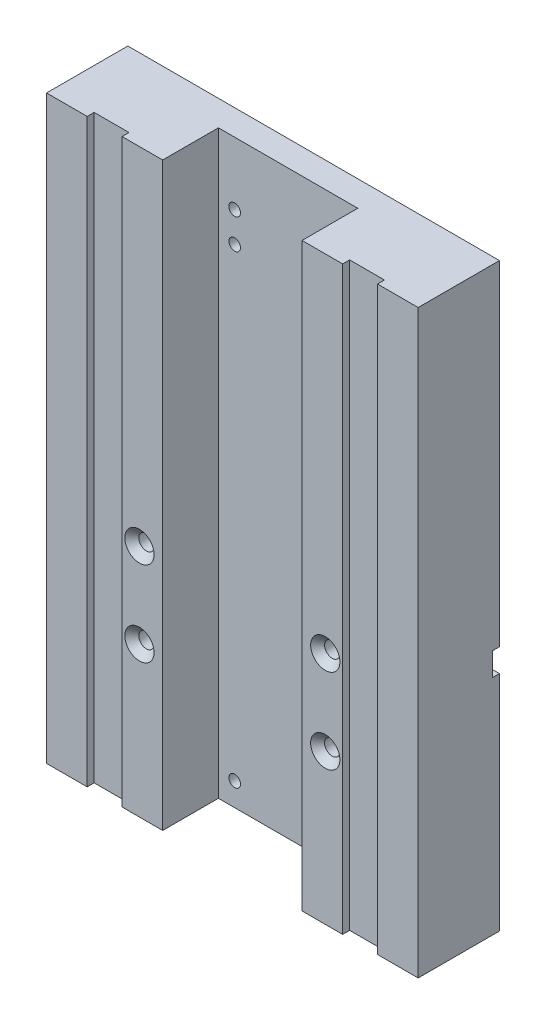
SolidWorks part; units mm, degrees
material "3.1355 (EN-AW 2024)"
ref_plane "Спереди" through (0, 0, 0) normal (0, 0, 1) x (1, 0, 0)
ref_plane "Сверху" through (0, 0, 0) normal (0, 1, 0) x (1, 0, 0)
ref_plane "Справа" through (0, 0, 0) normal (1, 0, 0) x (0, 0, -1)
sketch "Эскиз9" plane through (-20, 0, 0) normal (0, 0, -1) x (-1, 0, 0)
  line L1 (-100, 202) -> (60, 202)
  line L2 (-100, 202) -> (-100, -48)
  line L3 (-100, -48) -> (60, -48)
  line L4 (60, 202) -> (60, -48)
  point P4 (-20, 202)
  point P5 (-20, -48)
  dimension "D1" = 48
  dimension "D2" = 250
  dimension "D3" = 160
extrude "База" add sketch "Эскиз9" along normal blind 35
sketch "Эскиз14" plane through (0, 0, -35) normal (0, 0, -1) x (-1, 0, 0)
  line L0 (-80, 202) -> (-80, -48) construction
  line L1 (-80, 58) -> (80, 58)
  line L2 (-80, 58) -> (-80, 48)
  line L3 (-80, 48) -> (80, 48)
  line L4 (80, 58) -> (80, 48)
  line L5 (80, -48) -> (80, 202) construction
  line L6 (-80, -48) -> (80, -48) construction
  dimension "D1" = 10
  dimension "D2" = 96
extrude "Направляющая" cut sketch "Эскиз14" against normal blind 3
hole_wizard "К плите M6" positions "Эскиз12" profile "Эскиз13" countersink size "M6" standard "DIN" end condition through all
sketch "Эскиз12" plane through (0, 0, 0) normal (0, 0, 1) x (1, 0, 0)
  line L18 (-40, 53) -> (0, 53) construction
  line L19 (0, 53) -> (40, 53) construction
  line L22 (0, 53) -> (0, 58) construction
  line L23 (-80, 58) -> (80, 58) construction
  line L26 (0, 53) -> (0, 48) construction
  line L27 (80, 48) -> (-80, 48) construction
  point P0 (-40, 53)
  point P2 (40, 53)
  point P60 (-40, 16.5)
  point P62 (40, 16.5)
  dimension "D1" = 36.5
  dimension "D2" = 80
sketch "Эскиз13" plane through (-40, 53, 0) normal (1, 0, 0) x (0, -1, 0)
  line L0 (0, 0) -> (0, 35)
  line L1 (0, 35) -> (3.3, 35)
  line L2 (3.3, 35) -> (3.3, 3)
  line L3 (3.3, 3) -> (6.3, 0)
  line L5 (6.3, 0) -> (0, 0)
  line L6 (-3.3, 3) -> (-6.3, 0) construction
  line L11 (0, -6.35) -> (0, 107.95) construction
  dimension "Диаметр сквозного отверстия" = 6.6
  dimension "Глубина сквозного отверстия" = 35
  dimension "Диаметр передней зенковки" = 12.6
  dimension "Угол передней зенковки" = 90
sketch "Эскиз11" plane through (0, 0, 0) normal (0, 0, -1) x (-1, 0, 0)
  line L0 (80, 202) -> (-80, 202) construction
  line L1 (-30, 202) -> (30, 202)
  line L2 (-30, 202) -> (-30, -48)
  line L3 (-30, -48) -> (30, -48)
  line L4 (30, 202) -> (30, -48)
  line L5 (-80, -48) -> (80, -48) construction
  point P8 (0, 202)
  point P9 (0, -48)
  dimension "D1" = 60
extrude "Вырез-ШВП" cut sketch "Эскиз11" along normal blind 24
sketch "Эскиз15" plane through (0, 0, 0) normal (0, 0, 1) x (1, 0, 0)
  line L0 (-30, 102) -> (-47.5, 102) construction
  line L1 (-62.5, 252) -> (-47.5, 252)
  line L2 (-62.5, 252) -> (-62.5, -48)
  line L3 (-62.5, -48) -> (-47.5, -48)
  line L4 (-47.5, 252) -> (-47.5, -48)
  line L7 (62.5, 252) -> (47.5, 252)
  line L8 (62.5, 252) -> (62.5, -48)
  line L9 (62.5, -48) -> (47.5, -48)
  line L10 (47.5, 252) -> (47.5, -48)
  line L11 (-62.5, 102) -> (-80, 102) construction
  line L14 (-30, -48) -> (-80, -48) construction
  line L15 (47.5, 102) -> (30, 102) construction
  line L18 (62.5, 102) -> (80, 102) construction
  line L21 (80, 202) -> (80, -48) construction
  line L22 (30, 202) -> (30, -48) construction
  line L23 (-80, -48) -> (-80, 202) construction
  line L24 (-30, -48) -> (-30, 202) construction
  dimension "D1" = 15
  dimension "D3" = 300
extrude "Рельсы" cut sketch "Эскиз15" against normal blind 3
hole_wizard "Всободный конец ШВП - M6" positions "Эскиз16" profile "Эскиз17" tap size "M6" standard "DIN" end condition through all
sketch "Эскиз16" plane through (0, 0, -24) normal (0, 0, 1) x (1, 0, 0)
  line L0 (-23, -38) -> (0, -38) construction
  line L1 (0, -38) -> (23, -38) construction
  line L4 (30, -48) -> (-30, -48) construction
  point P0 (-23, -38)
  point P2 (23, -38)
  dimension "D1" = 46
  dimension "D2" = 10
sketch "Эскиз17" plane through (-23, -38, -24) normal (1, 0, 0) x (0, -1, 0)
  line L0 (0, 0) -> (0, 11)
  line L1 (0, 11) -> (2.5, 11)
  line L2 (2.5, 11) -> (2.5, 0)
  line L5 (2.5, 0) -> (0, 0)
  line L11 (0, -6.35) -> (0, 107.95) construction
  dimension "Диаметр проходного сверла" = 5
  dimension "Глубина проходного сверла" = 11
cosmetic thread "Отверстие резьбы1" parameters "D2"=6
cosmetic thread "Отверстие резьбы2" parameters "D2"=6
hole_wizard "КронштейнПодшипников" positions "Эскиз18" profile "Эскиз19" tap size "M6" standard "ISO" end condition through all
sketch "Эскиз18" plane through (0, 0, -24) normal (0, 0, 1) x (1, 0, 0)
  line L0 (-23, 162) -> (0, 162) construction
  line L1 (0, 162) -> (23, 162) construction
  point P0 (-23, 162)
  point P2 (23, 162)
  point P4 (-23, 175)
  point P6 (23, 175)
  dimension "D1" = 46
  dimension "D2" = 162
  dimension "D3" = 13
sketch "Эскиз19" plane through (-23, 162, -24) normal (1, 0, 0) x (0, -1, 0)
  line L0 (0, 0) -> (0, 11)
  line L1 (0, 11) -> (2.5, 11)
  line L2 (2.5, 11) -> (2.5, 0)
  line L5 (2.5, 0) -> (0, 0)
  line L11 (0, -6.35) -> (0, 107.95) construction
  dimension "Диаметр проходного сверла" = 5
  dimension "Глубина проходного сверла" = 11
cosmetic thread "Отверстие резьбы3" parameters "D1"=7, "D2"=6
cosmetic thread "Отверстие резьбы4" parameters "D1"=7, "D2"=6
cosmetic thread "Отверстие резьбы5" parameters "D1"=7, "D2"=6
cosmetic thread "Отверстие резьбы6" parameters "D1"=7, "D2"=6
